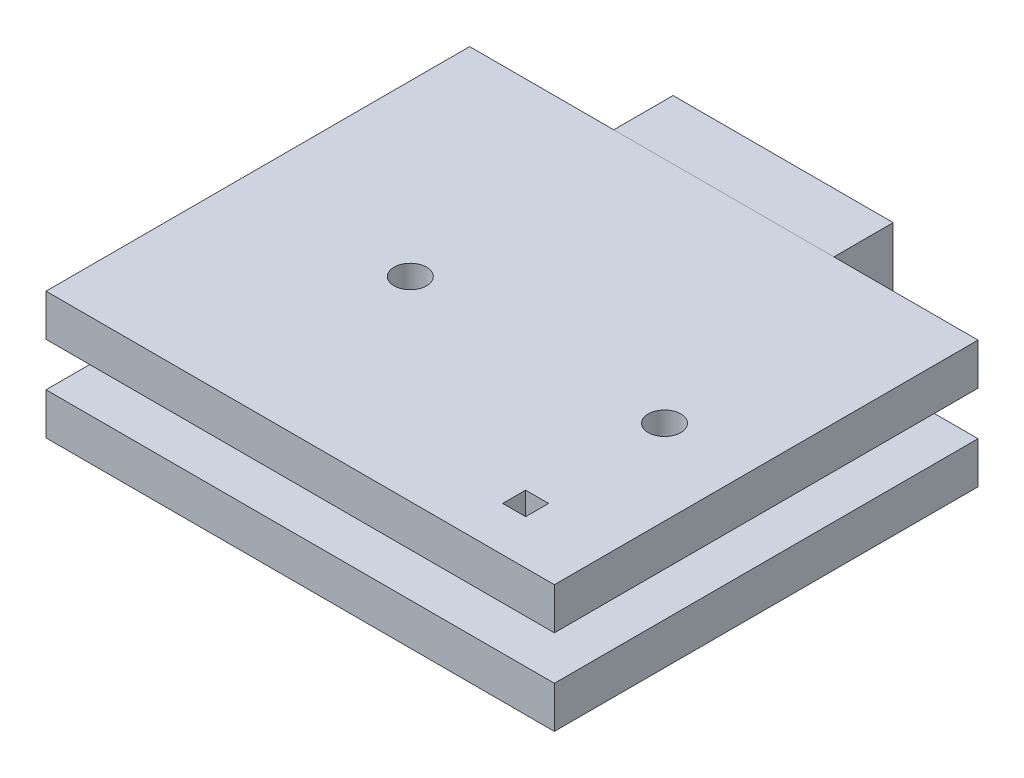
SolidWorks part; units mm, degrees
ref_plane "Front Plane" through (0, 0, 0) normal (0, 0, 1) x (1, 0, 0)
ref_plane "Top Plane" through (0, 0, 0) normal (0, 1, 0) x (1, 0, 0)
ref_plane "Right Plane" through (0, 0, 0) normal (1, 0, 0) x (0, 0, -1)
sketch "Sketch1" plane through (0, 0, 0) normal (0, 0, 1) x (1, 0, 0)
  line L1 (-38.1, 9.525) -> (38.1, 9.525)
  line L2 (-38.1, 9.525) -> (-38.1, -9.525)
  line L3 (-38.1, -9.525) -> (38.1, -9.525)
  line L4 (38.1, 9.525) -> (38.1, -9.525)
  line L5 (-38.1, 9.525) -> (38.1, -9.525) construction
  line L6 (-38.1, -9.525) -> (38.1, 9.525) construction
  point P0 (0, 0)
  dimension "D1" = 76.2
  dimension "D2" = 19.05
extrude "Boss-Extrude1" add sketch "Sketch1" along normal blind 63.5
sketch "Sketch2" plane through (0, 0, 0) normal (0, 0, -1) x (-1, 0, 0)
  line L0 (38.1, 9.525) -> (38.1, -9.525) construction
  line L1 (-38.1, -3.275) -> (38.1, -3.275)
  line L2 (-38.1, -3.275) -> (-38.1, 3.275)
  line L3 (-38.1, 3.275) -> (38.1, 3.275)
  line L4 (38.1, -3.275) -> (38.1, 3.275)
  line L5 (-38.1, -3.275) -> (38.1, 3.275) construction
  line L6 (-38.1, 3.275) -> (38.1, -3.275) construction
  point P0 (0, 0)
  dimension "D1" = 6.55
extrude "Cut-Extrude1" cut sketch "Sketch2" against normal blind 69.85
sketch "Sketch3" plane through (0, -9.525, 0) normal (0, -1, 0) x (1, 0, 0)
  line L0 (0, 63.5) -> (0, 34.29) construction
  line L1 (-38.1, 63.5) -> (38.1, 63.5) construction
  line L2 (38.1, 34.29) -> (25.4, 34.29) construction
  line L3 (38.1, 63.5) -> (38.1, 0) construction
  line L4 (-38.1, 34.29) -> (-12.7, 34.29) construction
  line L5 (-38.1, 63.5) -> (-38.1, 0) construction
  line L6 (25.4, 34.29) -> (25.4, 42.9695) construction
  line L7 (23.6783, 53.386) -> (27.1217, 53.386)
  line L8 (23.6783, 53.386) -> (23.6783, 56.8295)
  line L9 (23.6783, 56.8295) -> (27.1217, 56.8295)
  line L10 (27.1217, 53.386) -> (27.1217, 56.8295)
  line L11 (23.6783, 53.386) -> (27.1217, 56.8295) construction
  line L12 (23.6783, 56.8295) -> (27.1217, 53.386) construction
  line L14 (-38.1, 0) -> (38.1, 0) construction
  circle A0 centre (25.4, 34.29) radius 2.4349
  circle A1 centre (-12.7, 34.29) radius 2.4349
  point P17 (25.4, 55.1077)
  dimension "D3" = 4.8698
  dimension "D2" = 12.7
  dimension "D4" = 25.4
  dimension "D6" = 4.8698
  dimension "D1" = 34.29
sketch "Sketch4" plane through (0, 0, 0) normal (0, 0, -1) x (-1, 0, 0)
  line L0 (0, 9.525) -> (0, -9.525) construction
  line L1 (-38.1, 9.525) -> (38.1, 9.525) construction
  line L2 (38.1, -9.525) -> (-38.1, -9.525) construction
  line L4 (-16.4978, 9.525) -> (16.4978, 9.525)
  line L5 (-16.4978, 9.525) -> (-16.4978, -9.525)
  line L6 (-16.4978, -9.525) -> (16.4978, -9.525)
  line L7 (16.4978, 9.525) -> (16.4978, -9.525)
  line L8 (-16.4978, 9.525) -> (16.4978, -9.525) construction
  line L9 (-16.4978, -9.525) -> (16.4978, 9.525) construction
  point P6 (0, 0)
  dimension "D1" = 38.1
extrude "Boss-Extrude2" add sketch "Sketch4" along normal blind 8.89
sketch "Sketch6" plane through (0, 0, -8.89) normal (0, 0, -1) x (-1, 0, 0)
  line L1 (-10.16, 3.275) -> (10.16, 3.275)
  line L2 (-10.16, 3.275) -> (-10.16, -3.275)
  line L3 (-10.16, -3.275) -> (10.16, -3.275)
  line L4 (10.16, 3.275) -> (10.16, -3.275)
  line L5 (-10.16, 3.275) -> (10.16, -3.275) construction
  line L6 (-10.16, -3.275) -> (10.16, 3.275) construction
  point P0 (0, 0)
  dimension "D1" = 20.32
  dimension "D2" = 6.55
extrude "Cut-Extrude4" cut sketch "Sketch6" against normal blind 12.7
extrude "Cut-Extrude5" cut sketch "Sketch3" against normal through all both and the other way through all
equation "\"D1@Sketch2\"=0.25 + 0.00787402"
equation "\"D3@Sketch3\"=0.18385+0.00787402"
